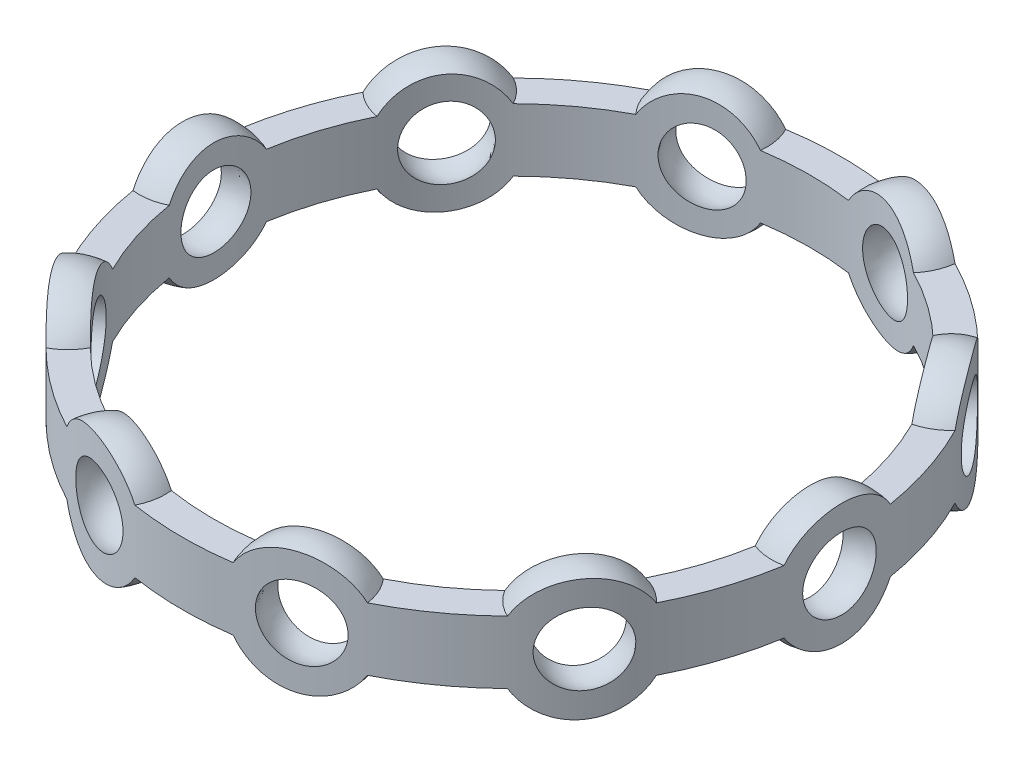
SolidWorks part; units mm, degrees
material "1.4511 (X3CrNb17)"
ref_plane "前视基准面" through (0, 0, 0) normal (0, 0, 1) x (1, 0, 0)
ref_plane "上视基准面" through (0, 0, 0) normal (0, 1, 0) x (1, 0, 0)
ref_plane "右视基准面" through (0, 0, 0) normal (1, 0, 0) x (0, 0, -1)
sketch "草图1" plane through (0, 0, 0) normal (0, 1, 0) x (1, 0, 0)
  circle A0 centre (0, 0) radius 10
  dimension "D1" = 20
extrude "凸台-拉伸1" add sketch "草图1" along normal mid plane 1
sketch "草图2" plane through (0, 0, 0) normal (0, 0, 1) x (1, 0, 0)
  line L0 (0, 12.6196) -> (0, -12.6196) construction
  line L2 (5, -1) -> (5, 1)
  arc A0 (5, -1) -> (5, 1) centre (5, 0) ccw
  point P4 (0, 0)
  dimension "D1" = 2
  dimension "D2" = 5
revolve "旋转1" add sketch "草图2" angle 360 about L2
pattern_circular "阵列(圆周)1" count 10 over 360 about axis through (-0.0378, 0, 0) along (0, 1, 0) of "旋转1"
sketch "草图3" plane through (0, 0.5, 0) normal (0, 1, 0) x (1, 0, 0)
  circle A0 centre (0, 0) radius 4.75
  circle A1 centre (0, 0) radius 5.25
  dimension "D1" = 9.5
  dimension "D2" = 10.5
extrude "切除-拉伸1" cut sketch "草图3" against normal mid plane 11.5 flip side to cut
sketch "草图4" plane through (0, 0, 0) normal (0, 0, 1) x (1, 0, 0)
  line L0 (5, -0.625) -> (5, 0.625)
  arc A0 (5, -0.625) -> (5, 0.625) centre (5, 0) ccw
  dimension "D1" = 1.25
  dimension "D2" = 5
revolve "切除-旋转1" cut sketch "草图4" angle 360 about L0
pattern_circular "阵列(圆周)2" count 10 over 360 about axis through (0, 0, 0) along (0, 1, 0) of "切除-旋转1"
equation "\"1.5.00mm\"=10"
